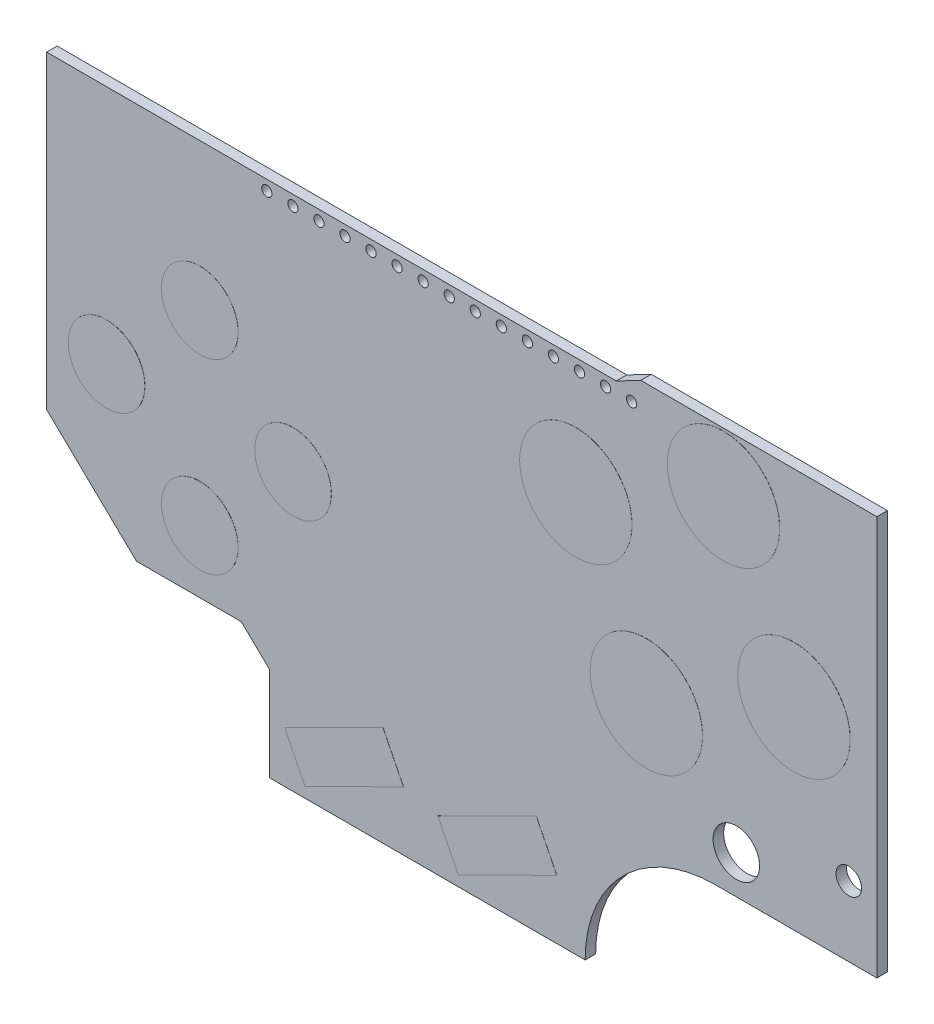
SolidWorks part; units mm, degrees
ref_plane "Front Plane" through (0, 0, 0) normal (0, 0, 1) x (1, 0, 0)
ref_plane "Top Plane" through (0, 0, 0) normal (0, 1, 0) x (1, 0, 0)
ref_plane "Right Plane" through (0, 0, 0) normal (1, 0, 0) x (0, 0, -1)
sketch "Sketch1" plane through (0, 0, 0) normal (0, 0, 1) x (1, 0, 0)
  line L0 (0, 0) -> (55.75, 0)
  line L1 (55.75, 0) -> (58.15, 1.25)
  line L2 (58.15, 1.25) -> (81.25, 1.25)
  line L3 (81.25, 1.25) -> (81.25, -37.85)
  line L4 (81.25, -37.85) -> (65.45, -37.85)
  line L5 (0, 0) -> (0, -30.3)
  line L6 (0, -30.3) -> (8.7926, -38.75)
  line L7 (8.7926, -38.75) -> (19.0426, -38.75)
  line L8 (19.0426, -38.75) -> (21.8, -41.4)
  line L9 (21.8, -41.4) -> (21.8, -50.6)
  line L10 (21.8, -50.6) -> (52.7, -50.6)
  arc A0 (65.45, -37.85) -> (52.7, -50.6) centre (65.45, -50.6) ccw
  point P14 (36.2171, 0)
  point P15 (0, -33.5503)
  point P16 (58.3231, 1.7858)
  point P17 (6.6385, -38.75)
  point P18 (21.8, -42.5553)
  point P19 (21.8, -40.2814)
  point P20 (21.8, -44.0551)
  dimension "D1" = 39.1
  dimension "D2" = 38.75
  dimension "D3" = 50.6
  dimension "D4" = 30.9
  dimension "D5" = 81.25
  dimension "D6" = 25.5
  dimension "D7" = 23.1
  dimension "D8" = 1.25
  dimension "D9" = 21.8
  dimension "D10" = 10.25
  dimension "D11" = 30.3
  dimension "D12" = 9.2
extrude "Boss-Extrude1" add sketch "Sketch1" along normal mid plane 1.03
sketch "Sketch3" plane through (0, 0, 0) normal (0, 0, 1) x (1, 0, 0)
  line L9 (15, -14.375) -> (15, -32.625) construction
  line L10 (24.125, -23.5) -> (5.875, -23.5) construction
  circle A4 centre (15, -14.375) radius 3.75
  circle A5 centre (15, -32.625) radius 3.75
  circle A6 centre (24.125, -23.5) radius 3.75
  circle A7 centre (5.875, -23.5) radius 3.75
  point P23 (15, -23.5)
  point P24 (15, -23.5)
  dimension "D3" = 14.375
  dimension "D10" = 7.5
  dimension "D2" = 5.875
  dimension "D9" = 18.25
sketch "Sketch2" plane through (0, 0, 0.515) normal (0, 0, 1) x (1, 0, 0)
  line L0 (66.25, -4.5) -> (51.7962, -11.4086) construction
  line L1 (66.25, -4.5) -> (73.15, -18.9357) construction
  line L2 (51.7962, -11.4086) -> (58.6962, -25.8443) construction
  line L3 (73.15, -18.9357) -> (58.6962, -25.8443) construction
  line L4 (81.25, -37.85) -> (81.25, 1.25) construction
  line L8 (81.25, 1.25) -> (58.15, 1.25) construction
  circle A0 centre (66.25, -4.5) radius 5.5
  circle A1 centre (73.15, -18.9357) radius 5.5
  circle A2 centre (58.6962, -25.8443) radius 5.5
  circle A3 centre (51.7962, -11.4086) radius 5.5
  dimension "D1" = 16.02
  dimension "D3" = 11
  dimension "D2" = 16
  dimension "D4" = 8.1
  dimension "D5" = 15
  dimension "D6" = 5.75
extrude "Boss-Extrude2" add sketch "Sketch2" along normal blind 0.01
extrude "Boss-Extrude5" add sketch "Sketch3" along normal through all
sketch "Sketch5" plane through (0, 0, 0.515) normal (0, 0, 1) x (1, 0, 0)
  line L0 (32.9189, -40.7735) -> (23.3, -45.5735)
  line L1 (32.9189, -40.7735) -> (34.9282, -44.8)
  line L2 (23.3, -45.5735) -> (25.3093, -49.6)
  line L3 (34.9282, -44.8) -> (25.3093, -49.6)
  line L4 (38.3, -45.5735) -> (40.3093, -49.6)
  line L5 (38.3, -45.5735) -> (47.9189, -40.7735)
  line L6 (40.3093, -49.6) -> (49.9282, -44.8)
  line L7 (47.9189, -40.7735) -> (49.9282, -44.8)
  line L8 (21.8, -41.4) -> (21.8, -50.6) construction
  line L9 (21.8, -50.6) -> (52.7, -50.6) construction
  dimension "D1" = 10.75
  dimension "D2" = 4.5
  dimension "D3" = 1.5
  dimension "D4" = 1
  dimension "D5" = 16.5
  dimension "D6" = 5.8
extrude "Boss-Extrude6" add sketch "Sketch5" along normal blind 0.01
sketch "Sketch6" plane through (0, 0, 0.515) normal (0, 0, 1) x (1, 0, 0)
  line L0 (81.25, -37.85) -> (81.25, 1.25) construction
  line L1 (55.75, 0) -> (0, 0) construction
  circle A0 centre (57.25, -1) radius 0.5
  dimension "D1" = 1
  dimension "D2" = 24
  dimension "D3" = 1
extrude "Cut-Extrude1" cut sketch "Sketch6" against normal through all
pattern_linear "LPattern1" count 15 spacing 2.55 along (-1, 0, 0) of "Cut-Extrude1"
sketch "Sketch7" plane through (0, 0, 0.515) normal (0, 0, 1) x (1, 0, 0)
  line L0 (65.45, -37.85) -> (81.25, -37.85) construction
  line L1 (81.25, -37.85) -> (81.25, 1.25) construction
  circle A0 centre (67.5, -34.1) radius 2.275
  circle A1 centre (78.5, -31) radius 1.25
  dimension "D1" = 4.55
  dimension "D4" = 2.5
  dimension "D2" = 3.75
  dimension "D3" = 13.75
  dimension "D5" = 2.75
  dimension "D6" = 6.85
extrude "Cut-Extrude2" cut sketch "Sketch7" against normal through all
